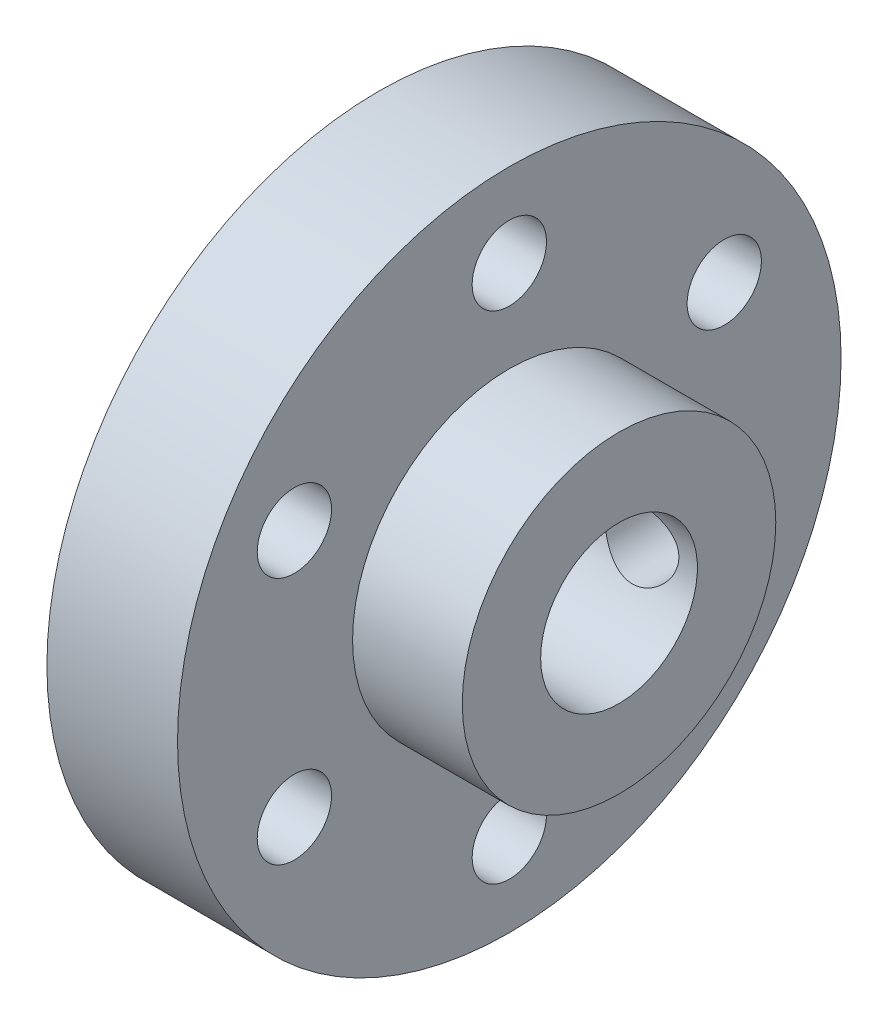
SolidWorks part; units mm, degrees
ref_plane "Front Plane" through (0, 0, 0) normal (0, 0, 1) x (1, 0, 0)
ref_plane "Top Plane" through (0, 0, 0) normal (0, 1, 0) x (1, 0, 0)
ref_plane "Right Plane" through (0, 0, 0) normal (1, 0, 0) x (0, 0, -1)
sketch "Sketch1" plane through (0, 0, 0) normal (1, 0, 0) x (0, 0, -1)
  circle A0 centre (0, 0) radius 12.7
  dimension "D1" = 25.4
extrude "Boss-Extrude1" add sketch "Sketch1" along normal blind 9.2
sketch "Sketch2" plane through (9.2, 0, 0) normal (1, 0, 0) x (0, 0, -1)
  circle A0 centre (0, 0) radius 12.7
  circle A1 centre (0, 0) radius 6
  dimension "D1" = 12
extrude "Cut-Extrude1" cut sketch "Sketch2" against normal blind 4.2
sketch "Sketch4" plane through (0, 0, 0) normal (-1, 0, 0) x (0, 0, 1)
  line L0 (-8.2272, 4.75) -> (0, 0) construction
  line L1 (0, 0) -> (-8.2272, -4.75) construction
  line L2 (0, -9.5) -> (0, 0) construction
  line L3 (8.2272, 4.75) -> (0, 0) construction
  line L4 (0, 9.5) -> (0, 0) construction
  line L5 (0, 0) -> (8.2272, -4.75) construction
  line L6 (0, 0) -> (0, 9.5) construction
  circle A0 centre (0, 0) radius 3
  circle A1 centre (0, 0) radius 9.5 construction
  circle A2 centre (-8.2272, -4.75) radius 1.4224
  circle A3 centre (8.2272, 4.75) radius 1.4224
  circle A4 centre (-8.2272, 4.75) radius 1.4224
  circle A5 centre (0, 9.5) radius 1.4224
  circle A6 centre (0, -9.5) radius 1.4224
  circle A7 centre (8.2272, -4.75) radius 1.4224
  point P16 (0, 0)
  dimension "D1" = 6
  dimension "D2" = 19
  dimension "D3" = 2.8448
  dimension "D4" = 60
  dimension "D5" = 60
  dimension "D6" = 60
  dimension "D7" = 60
  dimension "D8" = 60
extrude "Cut-Extrude2" cut sketch "Sketch4" against normal through all
sketch "Sketch5" plane through (0, 0, 0) normal (0, 0, 1) x (1, 0, 0)
  line L0 (0, 0) -> (4.9386, 0) construction
  line L2 (5, -6) -> (5, 6) construction
  line L3 (4.9386, 0) -> (9.2, 0) construction
  line L4 (9.2, -6) -> (9.2, 6) construction
  circle A0 centre (2.4693, 0) radius 1.4224
  circle A1 centre (7.0693, 0) radius 1.4224
  point P5 (5, 0)
  dimension "D1" = 2.8448
extrude "Cut-Extrude3" cut sketch "Sketch5" against normal through all
